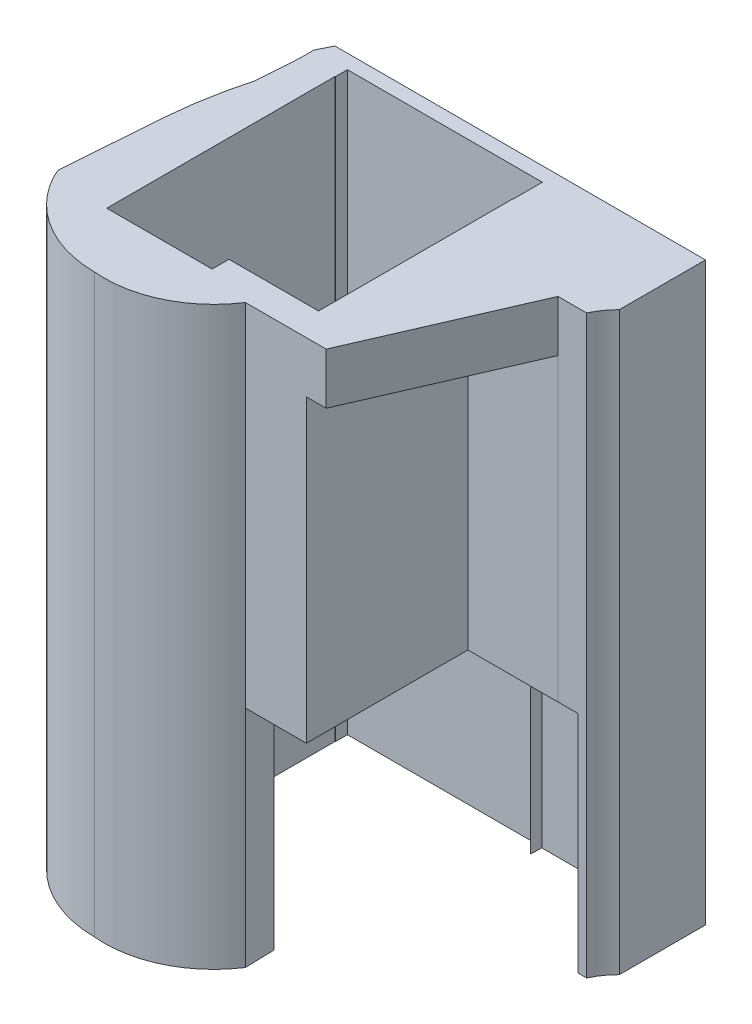
SolidWorks part; units mm, degrees
ref_plane "Front Plane" through (0, 0, 0) normal (0, 0, 1) x (1, 0, 0)
ref_plane "Top Plane" through (0, 0, 0) normal (0, 1, 0) x (1, 0, 0)
ref_plane "Right Plane" through (0, 0, 0) normal (1, 0, 0) x (0, 0, -1)
sketch "Sketch1" plane through (0, 0, 0) normal (0, 1, 0) x (1, 0, 0)
  line L0 (-21.9286, 20.53) -> (30.8194, 20.53)
  line L1 (30.8194, 20.53) -> (30.8194, 8.2695)
  line L2 (-21.9286, 20.53) -> (-22.9286, 18.53)
  line L3 (-22.9286, 18.53) -> (-22.9286, 16.53)
  line L4 (-22.9286, 16.53) -> (-23.3286, 10.53)
  line L5 (-23.3286, 10.53) -> (-24.1029, 7.4514)
  line L6 (-24.1029, 7.4514) -> (-24.8443, 3.4545)
  line L7 (-24.8443, 3.4545) -> (-25.2886, -0.5444)
  line L8 (-25.2886, -0.5444) -> (-26.3285, -14.47)
  line L9 (-26.3285, -14.47) -> (-25.9249, -15.432)
  line L10 (3.3204, -17.47) -> (14.82, -17.47)
  line L11 (14.82, -17.47) -> (24.8196, 5.53)
  line L12 (24.8196, 5.53) -> (28.8981, 5.53)
  arc A0 (-25.9249, -15.432) -> (-11.2183, -24.4463) centre (-11.1227, -7.7864) ccw
  arc A1 (-11.2183, -24.4463) -> (3.3204, -17.47) centre (-9.7241, -8.9225) ccw
  arc A2 (28.8981, 5.53) -> (30.8194, 8.2695) centre (37.5133, 1.5313) cw
extrude "Boss-Extrude1" add sketch "Sketch1" along normal blind 82
sketch "Sketch2" plane through (0, 0, 0) normal (0, -1, 0) x (1, 0, 0)
  line L0 (-18.1734, -16.7845) -> (-18.1734, 15.7155)
  line L1 (-18.1734, 15.7155) -> (-3.174, 15.7155)
  line L2 (-3.174, 15.7155) -> (-3.174, 13.3155)
  line L3 (-3.174, 13.3155) -> (9.5755, 13.3155)
  line L4 (9.5755, 13.3155) -> (9.5755, -14.3845)
  line L5 (9.5755, -14.3845) -> (-3.174, -14.3845)
  line L6 (-3.174, -14.3845) -> (-3.174, -16.7845)
  line L7 (-3.174, -16.7845) -> (-18.1734, -16.7845)
extrude "Cut-Extrude1" cut sketch "Sketch2" against normal blind 105
ref_plane "Plane1" through (40, 0, 0) normal (1, 0, 0) x (0, 0, -1)
ref_plane "Plane2" through (0, 90, 0) normal (0, 1, 0) x (1, 0, 0)
sketch "Sketch3" plane through (40, 0, 0) normal (1, 0, 0) x (0, 0, -1)
  line L0 (-17.47, 82) -> (-17.47, 75)
  line L1 (-17.4765, 31.7085) -> (5.5235, 31.7085)
  line L2 (5.5235, 31.7085) -> (5.5235, 74.7085)
  line L3 (5.5235, 74.7085) -> (-17.4765, 74.7085)
  line L4 (-17.4765, 74.7085) -> (-17.4765, 31.7085)
  line L5 (-17.47, 82) -> (-17.47, 0) construction
extrude "Cut-Extrude2" cut sketch "Sketch3" against normal blind 28 contours L2 L3 L4 L1
sketch "Sketch5" plane through (0, 0, 0) normal (0, -1, 0) x (1, 0, 0)
  line L0 (14.82, 17.47) -> (24.8196, -5.53)
  line L1 (24.8196, -5.53) -> (14.82, -5.53)
  line L2 (14.82, -5.53) -> (14.82, 17.47)
extrude "Cut-Extrude3" cut sketch "Sketch5" against normal blind 32
sketch "Sketch6" plane through (0, 0, 0) normal (0, -1, 0) x (1, 0, 0)
  line L11 (27.6681, -5.5215) -> (27.6681, -9.376)
  line L12 (14.82, -5.53) -> (27.6681, -5.5215)
  line L13 (14.82, 17.47) -> (14.82, -5.53)
  line L14 (3.3204, 17.47) -> (14.82, 17.47)
  line L15 (27.6681, -18.376) -> (27.6681, -9.376)
  line L16 (9.6681, -18.376) -> (27.6681, -18.376)
  line L17 (9.5755, -14.3845) -> (9.6681, -18.376)
  line L18 (9.5755, 13.3155) -> (9.5755, -14.3845)
  line L19 (3.2008, 13.3155) -> (9.5755, 13.3155)
  line L20 (3.3204, 17.47) -> (3.2008, 13.3155)
  line L21 (9.5755, 13.3155) -> (-3.174, 13.3155) construction
extrude "Cut-Extrude4" cut sketch "Sketch6" against normal blind 32
sketch "Sketch7" plane through (0, 0, 0) normal (0, -1, 0) x (1, 0, 0)
  line L0 (9.5755, -14.3845) -> (9.6681, -18.376) construction
  line L1 (-3.174, -14.3845) -> (9.6312, -14.3845)
  line L2 (-3.174, -14.3845) -> (-3.174, -16.7845)
  line L3 (-3.174, -16.7845) -> (9.6312, -16.7845)
  line L4 (9.6312, -14.3845) -> (9.6312, -16.7845)
  line L5 (-3.174, -14.3845) -> (9.6312, -16.7845) construction
  line L6 (-3.174, -16.7845) -> (9.6312, -14.3845) construction
  point P4 (3.2286, -15.5845)
extrude "Cut-Extrude5" cut sketch "Sketch7" against normal blind 89
sketch "Sketch8" plane through (0, 0, 0) normal (0, -1, 0) x (1, 0, 0)
  line L0 (9.6312, -16.7845) -> (9.6681, -18.376) construction
  line L5 (9.6312, -16.7845) -> (-18.1257, -16.7845)
  line L6 (9.6312, -16.7845) -> (9.6312, -18.4948)
  line L7 (9.6312, -18.4948) -> (-18.1257, -18.4948)
  line L8 (-18.1257, -16.7845) -> (-18.1257, -18.4948)
  line L9 (9.6312, -16.7845) -> (-18.1257, -18.4948) construction
  line L10 (9.6312, -18.4948) -> (-18.1257, -16.7845) construction
  line L11 (9.6312, -16.7845) -> (9.6312, -14.3845) construction
  point P4 (-4.2473, -17.6396)
extrude "Cut-Extrude6" cut sketch "Sketch8" against normal blind 89
